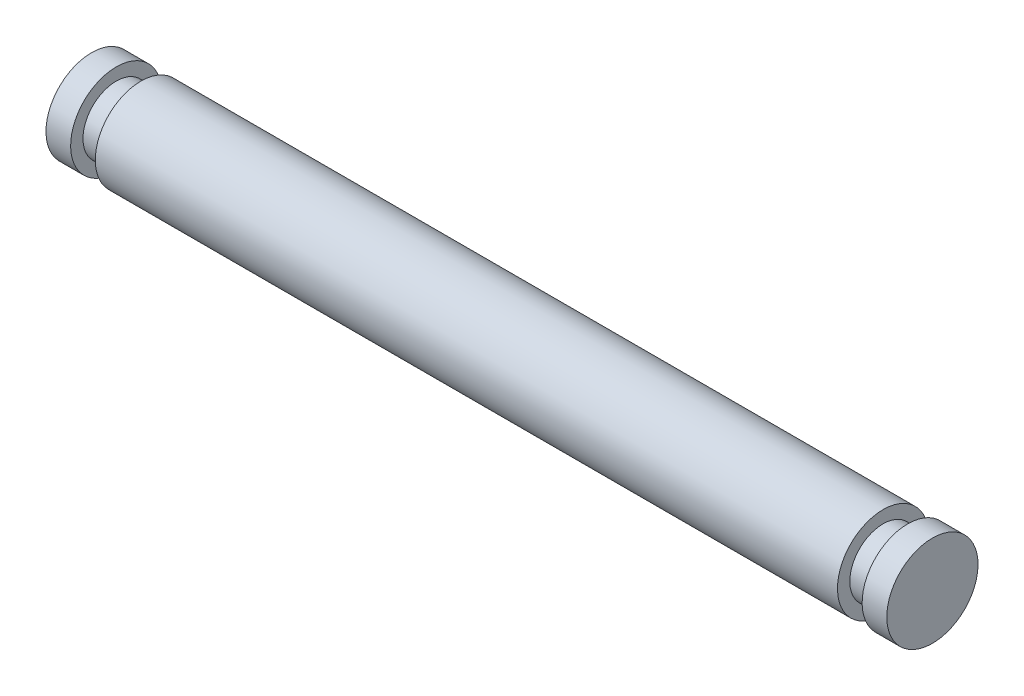
SolidWorks part; units mm, degrees
ref_plane "Front Plane" through (0, 0, 0) normal (0, 0, 1) x (1, 0, 0)
ref_plane "Top Plane" through (0, 0, 0) normal (0, 1, 0) x (1, 0, 0)
ref_plane "Right Plane" through (0, 0, 0) normal (1, 0, 0) x (0, 0, -1)
sketch "Sketch1" plane through (0, 0, 0) normal (0, 0, 1) x (1, 0, 0)
  line L0 (-30.1, 0) -> (30.1, 0)
  line L1 (30.1, 0) -> (30.1, -1)
  line L2 (30.1, -1) -> (32.1, -1)
  line L3 (32.1, -1) -> (32.1, 0)
  line L4 (32.1, 0) -> (34.1, 0)
  line L5 (34.1, 0) -> (34.1, -3.7)
  line L6 (34.1, -3.7) -> (-34.1, -3.7)
  line L7 (-34.1, -3.7) -> (-34.1, 0)
  line L8 (-34.1, 0) -> (-32.1, 0)
  line L9 (-32.1, 0) -> (-32.1, -1)
  line L10 (-32.1, -1) -> (-30.1, -1)
  line L11 (-30.1, -1) -> (-30.1, 0)
  point P3 (0, 0)
  point P14 (0, 0)
  point P15 (0, 0)
  point P16 (0, 0)
  point P17 (-30.1, -1)
  point P18 (-32.1, -0.6229)
  dimension "D1" = 60.2
  dimension "D2" = 3.7
  dimension "D3" = 1
  dimension "D4" = 2
  dimension "D5" = 2
revolve "Revolve1" add sketch "Sketch1" angle 360 about L6
